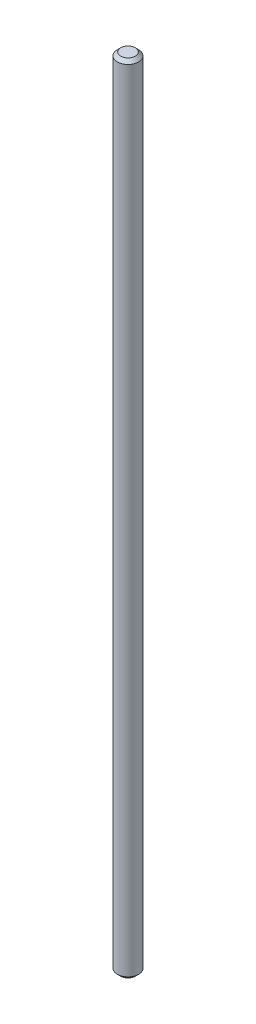
SolidWorks part; units mm, degrees
ref_plane "Front Plane" through (0, 0, 0) normal (0, 0, 1) x (1, 0, 0)
ref_plane "Top Plane" through (0, 0, 0) normal (0, 1, 0) x (1, 0, 0)
ref_plane "Right Plane" through (0, 0, 0) normal (1, 0, 0) x (0, 0, -1)
sketch "Sketch1" plane through (0, 0, 0) normal (0, 1, 0) x (1, 0, 0)
  circle A0 centre (0, 0) radius 4
  dimension "D1" = 8
extrude "Boss-Extrude1" add sketch "Sketch1" along normal blind 300
chamfer "Chamfer1" distance 1.25 angle 45 2 edges at (0, 0, 4) (0, 300, 4)
